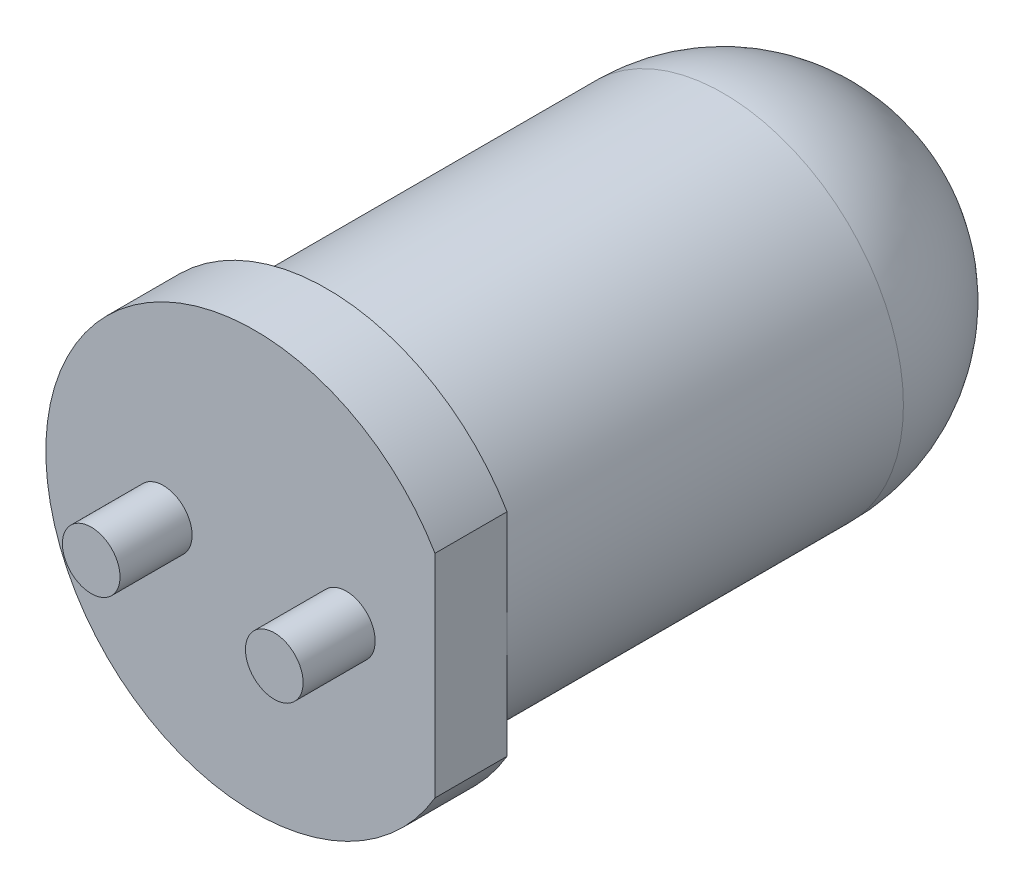
SolidWorks part; units mm, degrees
ref_plane "Front Plane" through (0, 0, 0) normal (0, 0, 1) x (1, 0, 0)
ref_plane "Top Plane" through (0, 0, 0) normal (0, 1, 0) x (1, 0, 0)
ref_plane "Right Plane" through (0, 0, 0) normal (1, 0, 0) x (0, 0, -1)
sketch "Sketch1" plane through (0, 0, 0) normal (0, 1, 0) x (1, 0, 0)
  line L0 (0, 0) -> (0, 9)
  line L1 (2.5, 6.5) -> (2.5, 1)
  line L2 (2.9, 0) -> (0, 0)
  line L3 (2.5, 1) -> (2.9, 1)
  line L4 (2.9, 1) -> (2.9, 0)
  arc A0 (0, 9) -> (2.5, 6.5) centre (0, 6.5) cw
  dimension "D1" = 2.5
  dimension "D2" = 2.9
  dimension "D3" = 1
  dimension "D4" = 9
revolve "Revolve1" add sketch "Sketch1" angle 360 about L0
sketch "Sketch2" plane through (0, 0, 0) normal (0, 0, 1) x (1, 0, 0)
  line L1 (2.9, 1.4697) -> (2.5, 1.4697)
  line L2 (2.9, 1.4697) -> (2.9, -1.4697)
  line L3 (2.9, -1.4697) -> (2.5, -1.4697)
  line L4 (2.5, 1.4697) -> (2.5, -1.4697)
  circle A0 centre (0, 0) radius 2.5 construction
  circle A1 centre (0, 0) radius 2.9 construction
extrude "Cut-Extrude1" cut sketch "Sketch2" against normal through all
sketch "Sketch3" plane through (0, 0, 0) normal (0, 0, 1) x (1, 0, 0)
  line L0 (0, 1.7562) -> (0, 0) construction
  line L1 (0, 0) -> (1.27, 0) construction
  circle A0 centre (1.27, 0) radius 0.4
  circle A1 centre (-1.27, 0) radius 0.4
  dimension "D1" = 0.8
  dimension "D2" = 1.27
extrude "Boss-Extrude1" add sketch "Sketch3" along normal blind 1
